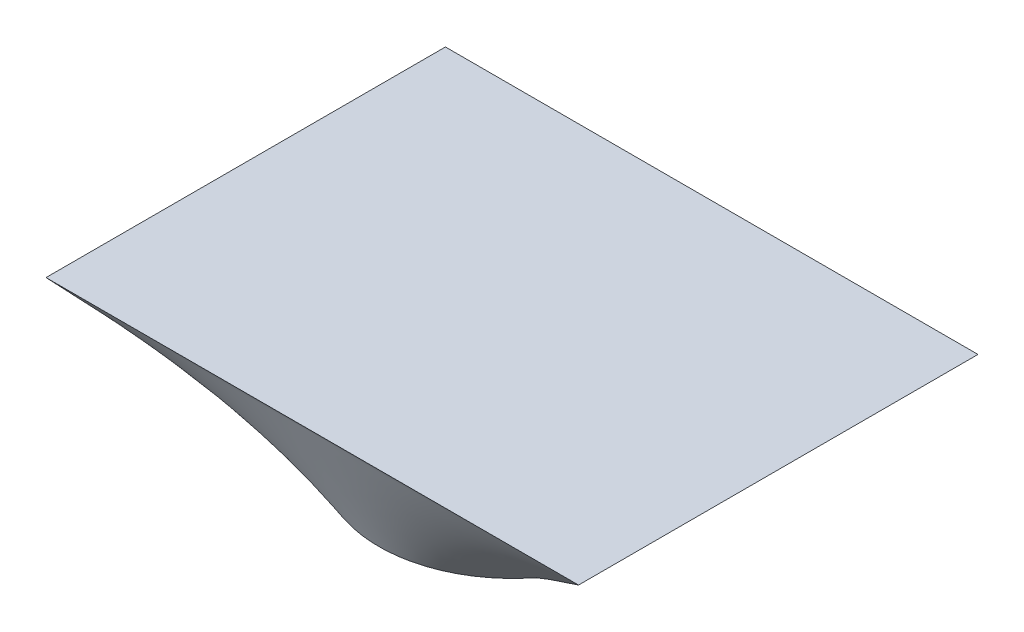
SolidWorks part; units mm, degrees
ref_plane "Ön Düzlem" through (0, 0, 0) normal (0, 0, 1) x (1, 0, 0)
ref_plane "Üst Düzlem" through (0, 0, 0) normal (0, 1, 0) x (1, 0, 0)
ref_plane "Sağ Düzlem" through (0, 0, 0) normal (1, 0, 0) x (0, 0, -1)
ref_plane "Düzlem1" through (0, 100, 0) normal (0, 1, 0) x (1, 0, 0)
sketch "Çizim4" plane through (0, 0, 0) normal (0, 1, 0) x (1, 0, 0)
  circle A0 centre (0, 0) radius 100
  circle A1 centre (0, -100) radius 1 construction
  dimension "D1" = 200
sketch "Çizim6" plane through (0, 100, 0) normal (0, 1, 0) x (1, 0, 0)
  line L1 (200, -150) -> (-200, -150)
  line L2 (200, -150) -> (200, 150)
  line L3 (200, 150) -> (-200, 150)
  line L4 (-200, -150) -> (-200, 150)
  line L5 (200, -150) -> (-200, 150) construction
  line L6 (200, 150) -> (-200, -150) construction
  circle A0 centre (0, -150) radius 1 construction
  point P0 (0, 0)
  dimension "D1" = 400
  dimension "D2" = 300
loft "Loft11" add profiles "Çizim4", "Çizim6"
